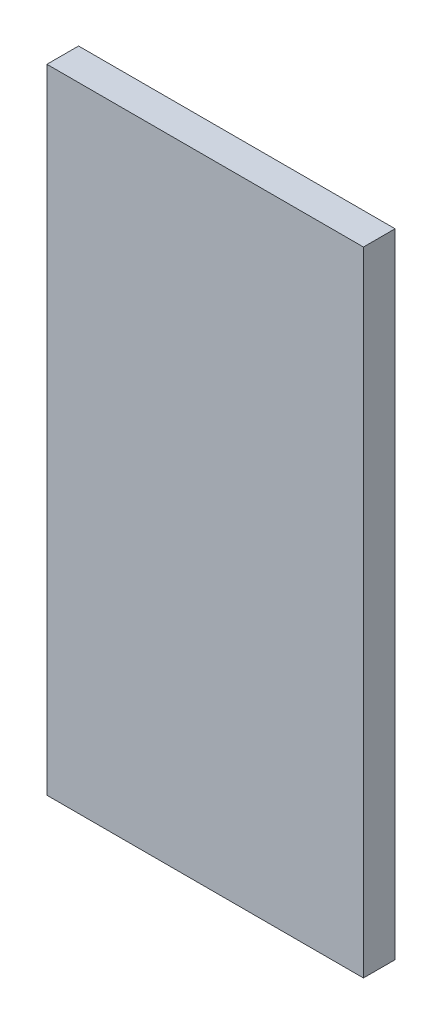
SolidWorks part; units mm, degrees
ref_plane "Front Plane" through (0, 0, 0) normal (0, 0, 1) x (1, 0, 0)
ref_plane "Top Plane" through (0, 0, 0) normal (0, 1, 0) x (1, 0, 0)
ref_plane "Right Plane" through (0, 0, 0) normal (1, 0, 0) x (0, 0, -1)
sketch "Sketch1" plane through (0, 0, 0) normal (0, 0, 1) x (1, 0, 0)
  line L1 (500, -1000) -> (-500, -1000)
  line L2 (500, -1000) -> (500, 1000)
  line L3 (500, 1000) -> (-500, 1000)
  line L4 (-500, -1000) -> (-500, 1000)
  line L5 (500, -1000) -> (-500, 1000) construction
  line L6 (500, 1000) -> (-500, -1000) construction
  point P0 (0, 0)
  dimension "D1" = 2000
  dimension "D2" = 1000
extrude "Boss-Extrude1" add sketch "Sketch1" along normal blind 100
